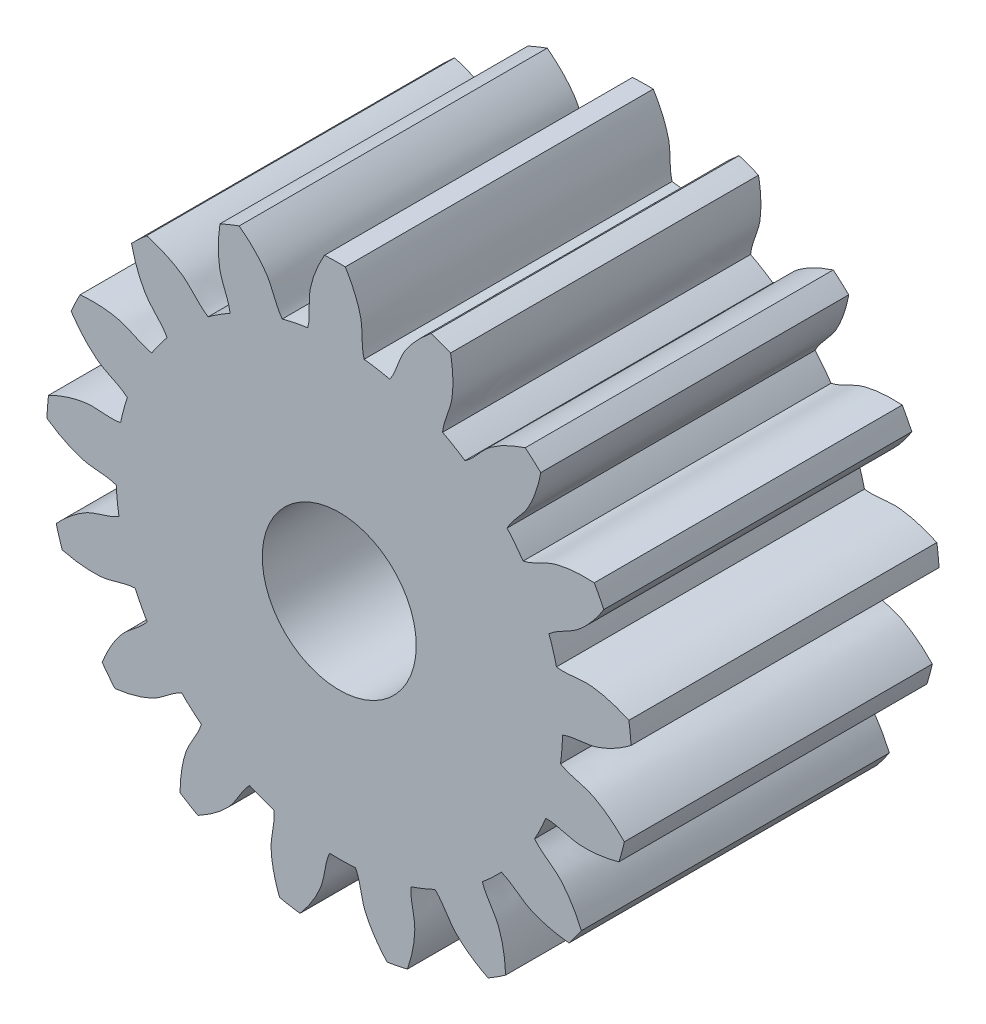
SolidWorks part; units mm, degrees
ref_plane "前视基准面" through (0, 0, 0) normal (0, 0, 1) x (1, 0, 0)
ref_plane "上视基准面" through (0, 0, 0) normal (0, 1, 0) x (1, 0, 0)
ref_plane "右视基准面" through (0, 0, 0) normal (1, 0, 0) x (0, 0, -1)
sketch "草图1" plane through (0, 0, 0) normal (0, 0, 1) x (1, 0, 0)
  circle A0 centre (0, 0) radius 14.5
  circle A1 centre (0, 0) radius 5
extrude "凸台-拉伸1" add sketch "草图1" along normal blind 20
sketch "草图2" plane through (0, 0, 0) normal (0, 0, 1) x (1, 0, 0)
  arc A0 (18.8067, 2.7036) -> (18.951, 1.3635) centre (0, 0) cw
  arc A1 (14.1058, 3.3579) -> (14.4974, -0.2769) centre (0, 0) cw
  spline S0 degree 3 poles (18.951, 1.3635) (18.5795, 1.0858) (18.0039, 0.708) (17.1929, 0.3216) (16.1208, -0.082) (15.1602, -0.0216) (14.4974, -0.2769) knots 0 0 0 0 0.289468 0.427045 0.559834 1 1 1 1
  spline S1 degree 3 poles (18.8067, 2.7036) (18.3845, 2.8959) (17.7417, 3.1424) (16.867, 3.3473) (15.7335, 3.5133) (14.8079, 3.2497) (14.1058, 3.3579) knots 0 0 0 0 0.289468 0.427045 0.559834 1 1 1 1
extrude "凸台-拉伸2" add sketch "草图2" along normal blind 20
pattern_circular "阵列(圆周)1" count 17 over 360 about axis through (0, 0, 20) along (0, 0, -1) of "凸台-拉伸2"
